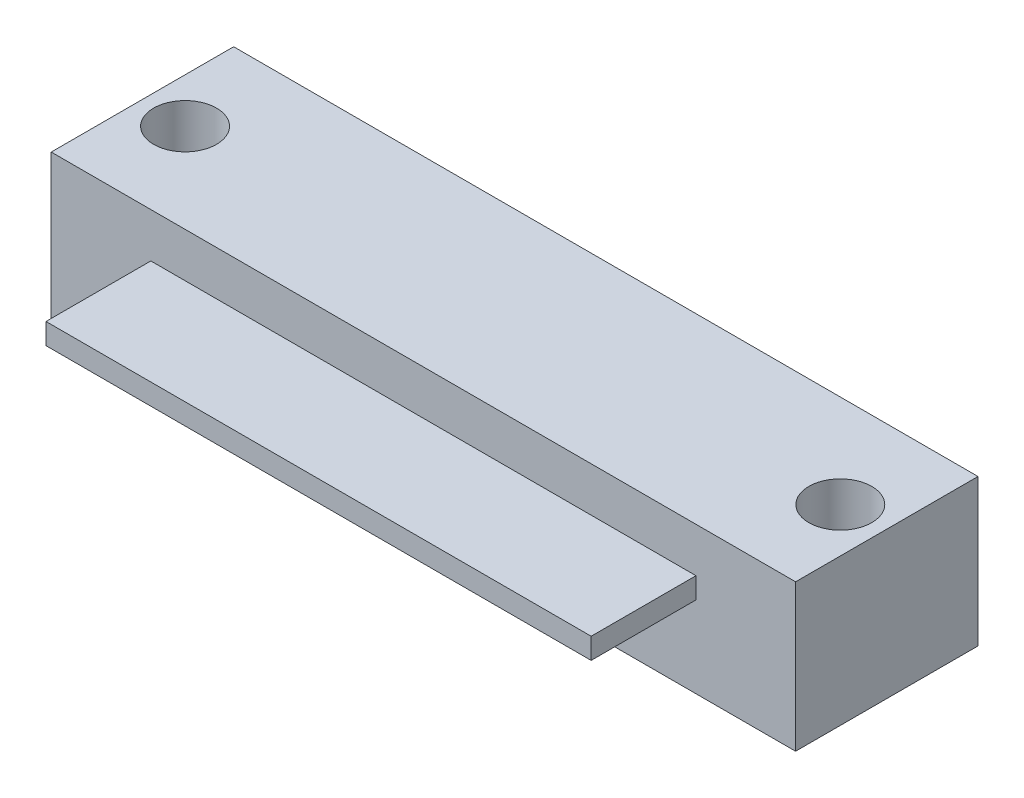
SolidWorks part; units mm, degrees
ref_plane "Front Plane" through (0, 0, 0) normal (0, 0, 1) x (1, 0, 0)
ref_plane "Top Plane" through (0, 0, 0) normal (0, 1, 0) x (1, 0, 0)
ref_plane "Right Plane" through (0, 0, 0) normal (1, 0, 0) x (0, 0, -1)
sketch "Sketch2" plane through (0, 0, 0) normal (0, 1, 0) x (1, 0, 0)
  line L1 (0, 0) -> (90.17, 0)
  line L2 (0, 0) -> (0, 22.098)
  line L3 (0, 22.098) -> (90.17, 22.098)
  line L4 (90.17, 0) -> (90.17, 22.098)
  dimension "D1" = 90.17
  dimension "D2" = 22.098
extrude "Boss-Extrude1" add sketch "Sketch2" along normal blind 17.78
sketch "Sketch3" plane through (0, 0, 0) normal (0, 0, 1) x (1, 0, 0)
  line L0 (0, 17.78) -> (90.17, 17.78) construction
  line L1 (12.065, 9.8476) -> (78.105, 9.8476)
  line L2 (12.065, 9.8476) -> (12.065, 12.3876)
  line L3 (12.065, 12.3876) -> (78.105, 12.3876)
  line L4 (78.105, 9.8476) -> (78.105, 12.3876)
  line L5 (12.065, 9.8476) -> (78.105, 12.3876) construction
  line L6 (12.065, 12.3876) -> (78.105, 9.8476) construction
  point P0 (45.085, 11.1176)
  point P8 (45.085, 17.78)
  dimension "D1" = 66.04
  dimension "D2" = 2.54
extrude "Boss-Extrude2" add sketch "Sketch3" along normal blind 12.7
sketch "Sketch4" plane through (0, 17.78, 0) normal (0, 1, 0) x (1, 0, 0)
  line L0 (5.3975, 10.8149) -> (0, 10.8149) construction
  line L1 (0, 22.098) -> (0, 0) construction
  line L2 (84.7725, 10.8149) -> (90.17, 10.8149) construction
  line L3 (90.17, 0) -> (90.17, 22.098) construction
  point P0 (5.3975, 10.8149)
  point P1 (84.7725, 10.8149)
  dimension "D1" = 5.3975
hole_wizard "CBORE for #8 Binding Head Machine Screw1" positions "Sketch5" profile "Sketch6" counterbore size "#8" standard "ANSI Inch" end condition through all
sketch "Sketch5" plane through (0, 17.78, 0) normal (0, 1, 0) x (1, 0, 0)
  point P0 (5.3975, 10.8149)
  point P3 (84.7725, 10.8149)
sketch "Sketch6" plane through (5.3975, 17.78, -10.8149) normal (1, 0, 0) x (0, 0, 1)
  line L0 (0, 0) -> (0, 17.78)
  line L1 (0, 17.78) -> (1.905, 17.78)
  line L3 (1.905, 17.78) -> (1.905, 11.176)
  line L4 (1.905, 11.176) -> (3.81, 11.176)
  line L5 (3.81, 11.176) -> (3.81, 0)
  line L7 (3.81, 0) -> (0, 0)
  line L11 (0, -6.35) -> (0, 107.95) construction
  dimension "Thru Hole Dia." = 3.81
  dimension "Thru Hole Depth" = 17.78
  dimension "C'Bore Dia." = 7.62
  dimension "C'Bore Depth" = 11.176
